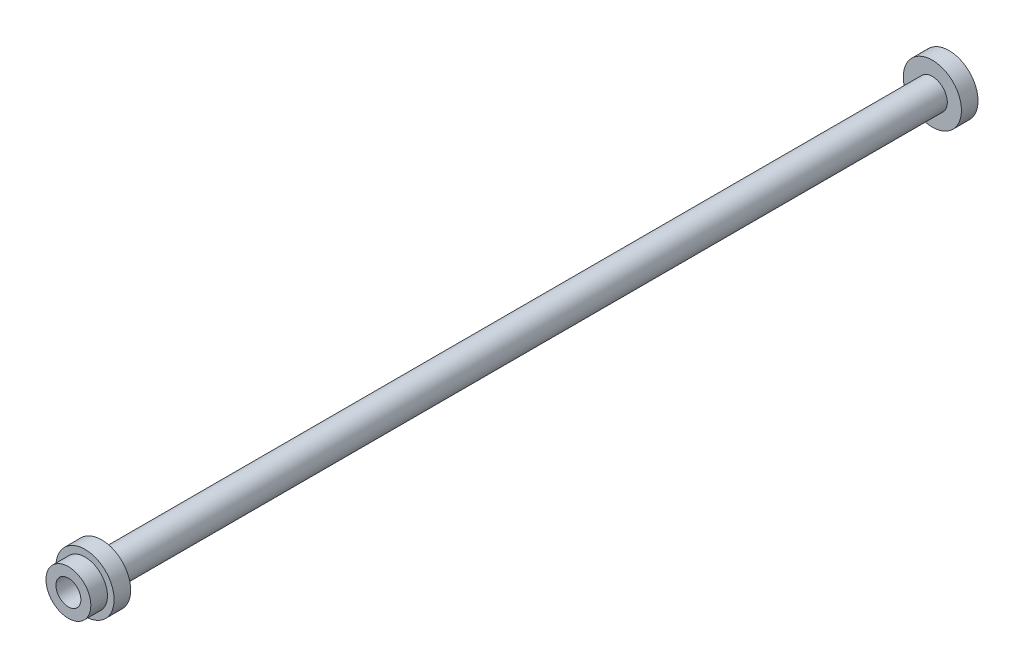
SolidWorks part; units mm, degrees
material "Rubber"
ref_plane "Front Plane" through (0, 0, 0) normal (0, 0, 1) x (1, 0, 0)
ref_plane "Top Plane" through (0, 0, 0) normal (0, 1, 0) x (1, 0, 0)
ref_plane "Right Plane" through (0, 0, 0) normal (1, 0, 0) x (0, 0, -1)
sketch "Sketch1" plane through (0, 0, 0) normal (0, 0, 1) x (1, 0, 0)
  circle A0 centre (0, 0) radius 9
  circle A1 centre (0, 0) radius 7.5
  dimension "D1" = 15
  dimension "D2" = 18
extrude "Boss-Extrude1" add sketch "Sketch1" along normal blind 530
sketch "Sketch2" plane through (0, 0, 0) normal (0, 0, -1) x (-1, 0, 0)
  circle A0 centre (0, 0) radius 7.5
  circle A1 centre (0, 0) radius 17.5
  dimension "D1" = 15
  dimension "D2" = 35
extrude "Boss-Extrude2" add sketch "Sketch2" against normal blind 10
sketch "Sketch3" plane through (0, 0, 530) normal (0, 0, 1) x (1, 0, 0)
  circle A0 centre (0, 0) radius 17.5
  circle A1 centre (0, 0) radius 7.5
  dimension "D1" = 15
  dimension "D2" = 35
extrude "Boss-Extrude3" add sketch "Sketch3" against normal blind 20
sketch "Sketch4" plane through (0, 0, 530) normal (0, 0, 1) x (1, 0, 0)
  circle A0 centre (0, 0) radius 13.5
  circle A1 centre (0, 0) radius 17.5
  dimension "D1" = 27
  dimension "D2" = 35
extrude "Cut-Extrude1" cut sketch "Sketch4" against normal blind 10
